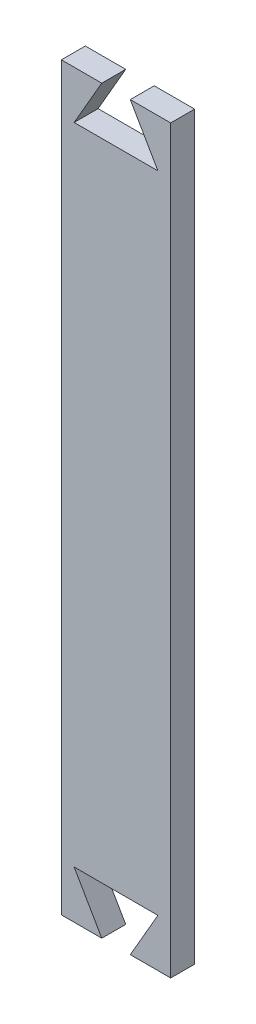
SolidWorks part; units mm, degrees
material "Custom Plastic"
ref_plane "X-Y Datum" through (0, 0, 0) normal (0, 0, 1) x (1, 0, 0)
ref_plane "X-Z Datum" through (0, 0, 0) normal (0, 1, 0) x (1, 0, 0)
ref_plane "Y-Z Datum" through (0, 0, 0) normal (1, 0, 0) x (0, 0, -1)
sketch "Sketch1" plane through (0, 0, 0) normal (0, 0, 1) x (1, 0, 0)
  line L0 (-3.0241, 0) -> (-8.89, 10.16)
  line L1 (-8.89, 10.16) -> (8.89, 10.16)
  line L2 (8.89, 10.16) -> (3.0241, 0)
  line L3 (3.0241, 0) -> (11.5976, 0)
  line L4 (11.5976, 0) -> (11.5976, 157.1625)
  line L5 (-3.0241, 0) -> (-11.5976, 0)
  line L6 (-11.5976, 0) -> (-11.5976, 157.1625)
  line L7 (-11.5976, 0) -> (11.5976, 0) construction
  line L8 (11.5976, 157.1625) -> (3.0241, 157.1625)
  line L9 (-11.5976, 78.5812) -> (11.5976, 78.5812) construction
  line L10 (8.89, 147.0025) -> (3.0241, 157.1625)
  line L11 (-8.89, 147.0025) -> (8.89, 147.0025)
  line L12 (-3.0241, 157.1625) -> (-8.89, 147.0025)
  line L13 (-3.0241, 157.1625) -> (-11.5976, 157.1625)
  point P7 (0, 0)
  point P9 (0, 10.16)
  dimension "D1" = 60
  dimension "D2" = 10.16
  dimension "D3" = 60
  dimension "D4" = 17.78
  dimension "D5" = 23.1952
  dimension "D6" = 157.1625
extrude "Boss-Extrude1" add sketch "Sketch1" along normal blind 5.08
